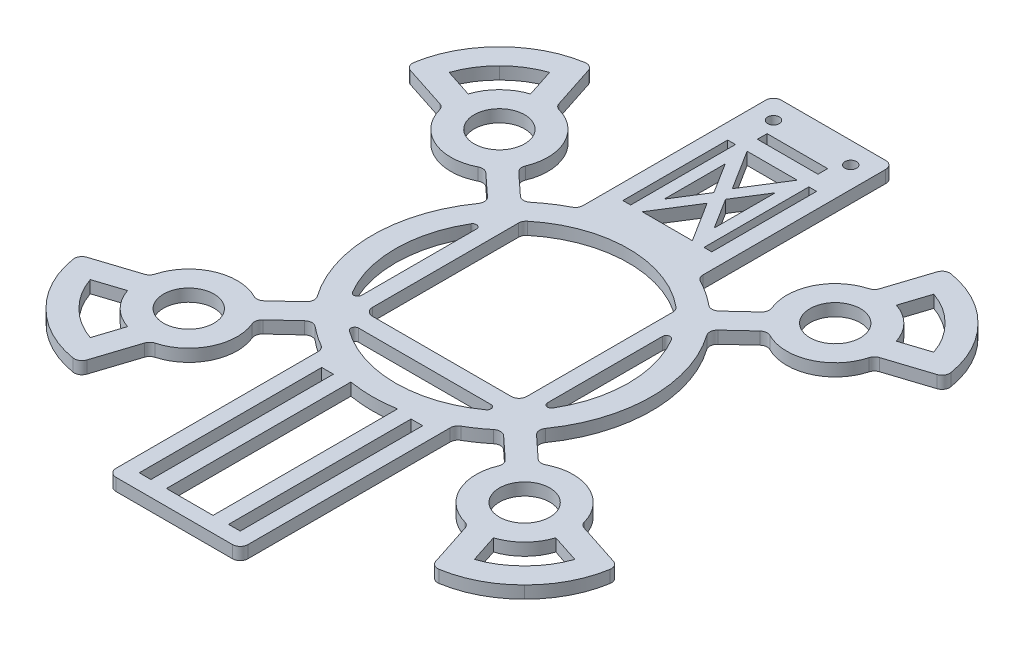
SolidWorks part; units mm, degrees
material "Mahogany"
ref_plane "Front Plane" through (0, 0, 0) normal (0, 0, 1) x (1, 0, 0)
ref_plane "Top Plane" through (0, 0, 0) normal (0, 1, 0) x (1, 0, 0)
ref_plane "Right Plane" through (0, 0, 0) normal (1, 0, 0) x (0, 0, -1)
sketch "DroneShadow" plane through (0, 0, 0) normal (0, 1, 0) x (1, 0, 0)
  line L0 (43.25, 80) -> (43.25, 0) construction
  line L5 (0, 0) -> (86.5, 0) construction
  line L6 (0, 0) -> (0, 80) construction
  line L7 (0, 80) -> (86.5, 80) construction
  line L8 (86.5, 0) -> (86.5, 80) construction
  line L9 (27.25, 76) -> (59.25, 76) construction
  line L10 (27.25, 76) -> (27.25, 12) construction
  line L11 (27.25, 12) -> (59.25, 12) construction
  line L12 (59.25, 76) -> (59.25, 12) construction
  line L13 (0, 80) -> (-14.1421, 94.1421) construction
  line L14 (0, 80) -> (-6.2176, 99.1576) construction
  line L15 (0, 80) -> (-19.1576, 86.2176) construction
  line L16 (0, 40) -> (86.5, 40) construction
  line L17 (0, 0) -> (-19.1576, -6.2176) construction
  line L18 (0, 0) -> (-6.2176, -19.1576) construction
  line L19 (0, 0) -> (-14.1421, -14.1421) construction
  line L20 (86.5, 0) -> (100.6421, -14.1421) construction
  line L21 (86.5, 0) -> (92.7176, -19.1576) construction
  line L22 (86.5, 0) -> (105.6576, -6.2176) construction
  line L23 (86.5, 80) -> (105.6576, 86.2176) construction
  line L24 (86.5, 80) -> (92.7176, 99.1576) construction
  line L25 (86.5, 80) -> (100.6421, 94.1421) construction
  circle A0 centre (0, 80) radius 5.5 construction
  arc A4 (-14.1421, 94.1421) -> (-6.2176, 99.1576) centre (0.358, 80) cw construction
  arc A5 (-14.1421, 94.1421) -> (-19.1576, 86.2176) centre (0, 79.642) ccw construction
  arc A6 (-14.1421, -14.1421) -> (-19.1576, -6.2176) centre (0, 0.358) cw construction
  arc A7 (-14.1421, -14.1421) -> (-6.2176, -19.1576) centre (0.358, 0) ccw construction
  circle A8 centre (0, 0) radius 5.5 construction
  circle A9 centre (86.5, 0) radius 5.5 construction
  arc A10 (100.6421, -14.1421) -> (92.7176, -19.1576) centre (86.142, 0) cw construction
  arc A11 (100.6421, -14.1421) -> (105.6576, -6.2176) centre (86.5, 0.358) ccw construction
  arc A12 (100.6421, 94.1421) -> (105.6576, 86.2176) centre (86.5, 79.642) cw construction
  arc A13 (100.6421, 94.1421) -> (92.7176, 99.1576) centre (86.142, 80) ccw construction
  circle A14 centre (86.5, 80) radius 5.5 construction
  point P12 (43.25, 76)
  dimension "D1" = 80
  dimension "D2" = 86.5
  dimension "D3" = 64
  dimension "D4" = 32
  dimension "D5" = 4
  dimension "D6" = 45
  dimension "D7" = 20
  dimension "D8" = 18.3
sketch "Sketch2" plane through (0, 0, 0) normal (0, 1, 0) x (1, 0, 0)
  line L0 (0, 40) -> (86.5, 40) construction
  line L1 (43.25, 80) -> (43.25, 0) construction
  line L2 (0, 40) -> (86.5, 40) construction
  line L3 (18.9494, 66.5609) -> (10.9456, 73.9632)
  line L4 (43.25, 80) -> (43.25, 0) construction
  line L5 (0, 80) -> (-14.1421, 94.1421) construction
  line L6 (0, 80) -> (-12.3659, 95.7593) construction
  line L15 (0, 80) -> (43.25, 40) construction
  line L16 (27.25, 76) -> (59.25, 76) construction
  line L17 (14.8755, 62.156) -> (6.8717, 69.5583)
  line L18 (14.8755, 62.156) -> (19.2989, 58.065) construction
  line L19 (27.25, 76) -> (59.25, 76) construction
  line L20 (18.9494, 66.5609) -> (23.3728, 62.4699) construction
  line L21 (-14.1421, -14.1421) -> (0, 0) construction
  line L22 (0, 80) -> (-15.7593, 92.3659) construction
  line L23 (-14.1421, 94.1421) -> (0, 80) construction
  line L24 (-15.7593, 92.3659) -> (-9.8339, 87.7164)
  line L25 (2.3218, 92.2825) -> (-2.1731, 106.1324)
  line L26 (-12.3659, 95.7593) -> (-7.7164, 89.8339)
  line L27 (9.3391, 70.6609) -> (-2.1731, 106.1324)
  line L28 (-26.1324, 82.1731) -> (9.3391, 70.6609)
  line L30 (-26.1324, 82.1731) -> (-12.2825, 77.6782)
  line L31 (0, 80) -> (-6.2176, 99.1576) construction
  line L33 (-3.8587, 91.8895) -> (-6.2176, 99.1576)
  line L34 (-11.8895, 83.8587) -> (-19.1576, 86.2176)
  line L35 (0, 0) -> (-15.7593, -12.3659) construction
  line L36 (18.9494, 13.4391) -> (23.3728, 17.5301) construction
  line L37 (14.8755, 17.844) -> (19.2989, 21.935) construction
  line L38 (0, 0) -> (-12.3659, -15.7593) construction
  line L39 (-11.8895, -3.8587) -> (-19.1576, -6.2176)
  line L40 (-3.8587, -11.8895) -> (-6.2176, -19.1576)
  line L41 (-26.1324, -2.1731) -> (-12.2825, 2.3218)
  line L42 (-12.3659, -15.7593) -> (-7.7164, -9.8339)
  line L43 (2.3218, -12.2825) -> (-2.1731, -26.1324)
  line L44 (-15.7593, -12.3659) -> (-9.8339, -7.7164)
  line L45 (14.8755, 17.844) -> (6.8717, 10.4417)
  line L46 (18.9494, 13.4391) -> (10.9456, 6.0368)
  line L47 (19.2989, 58.065) -> (19.2989, 21.935)
  line L48 (23.3728, 62.4699) -> (23.3728, 17.5301)
  line L49 (19.2989, 21.935) -> (67.2011, 21.935)
  line L50 (23.3728, 17.5301) -> (63.1272, 17.5301)
  line L51 (84.1782, -12.2825) -> (88.6731, -26.1324)
  line L52 (86.5, 0) -> (98.8659, -15.7593) construction
  line L53 (71.6245, 17.844) -> (67.2011, 21.935) construction
  line L54 (67.5506, 13.4391) -> (63.1272, 17.5301) construction
  line L55 (86.5, 0) -> (102.2593, -12.3659) construction
  line L56 (100.6421, 94.1421) -> (86.5, 80) construction
  line L57 (86.5, 80) -> (102.2593, 92.3659) construction
  line L58 (100.6421, -14.1421) -> (86.5, 0) construction
  line L59 (67.5506, 66.5609) -> (63.1272, 62.4699) construction
  line L60 (71.6245, 62.156) -> (67.2011, 58.065) construction
  line L61 (86.5, 80) -> (43.25, 40) construction
  line L62 (86.5, 80) -> (98.8659, 95.7593) construction
  line L63 (63.1272, 62.4699) -> (63.1272, 17.5301)
  line L64 (67.2011, 58.065) -> (67.2011, 21.935)
  line L65 (67.5506, 13.4391) -> (75.5544, 6.0368)
  line L66 (71.6245, 17.844) -> (79.6283, 10.4417)
  line L67 (102.2593, -12.3659) -> (96.3339, -7.7164)
  line L68 (98.8659, -15.7593) -> (94.2164, -9.8339)
  line L69 (112.6324, -2.1731) -> (98.7825, 2.3218)
  line L70 (90.3587, -11.8895) -> (92.7176, -19.1576)
  line L71 (98.3895, -3.8587) -> (105.6576, -6.2176)
  line L72 (98.3895, 83.8587) -> (105.6576, 86.2176)
  line L73 (90.3587, 91.8895) -> (92.7176, 99.1576)
  line L74 (112.6324, 82.1731) -> (98.7825, 77.6782)
  line L75 (98.8659, 95.7593) -> (94.2164, 89.8339)
  line L76 (84.1782, 92.2825) -> (88.6731, 106.1324)
  line L77 (102.2593, 92.3659) -> (96.3339, 87.7164)
  line L78 (71.6245, 62.156) -> (79.6283, 69.5583)
  line L79 (67.5506, 66.5609) -> (75.5544, 73.9632)
  circle A8 centre (43.25, 40) radius 36
  circle A9 centre (0, 80) radius 12.5
  circle A13 centre (43.25, 40) radius 30
  circle A14 centre (0, 80) radius 6.5
  circle A15 centre (0, 80) radius 6.5
  arc A18 (-6.2176, -19.1576) -> (-14.1421, -14.1421) centre (0.358, 0) cw
  arc A19 (-14.1421, 94.1421) -> (-19.1576, 86.2176) centre (0, 79.642) ccw construction
  arc A20 (-6.2176, 99.1576) -> (-14.1421, 94.1421) centre (0.358, 80) ccw construction
  arc A21 (-2.1731, 106.1324) -> (-18.385, 98.385) centre (0.358, 80) ccw
  arc A22 (-18.385, 98.385) -> (-26.1324, 82.1731) centre (0, 79.642) ccw
  arc A23 (-2.1731, 106.1324) -> (-18.385, 98.385) centre (0.358, 80) ccw
  arc A24 (-18.385, 98.385) -> (-26.1324, 82.1731) centre (0, 79.642) ccw
  arc A25 (-14.1421, 94.1421) -> (-19.1576, 86.2176) centre (0, 79.642) ccw
  arc A26 (-6.2176, 99.1576) -> (-14.1421, 94.1421) centre (0.358, 80) ccw
  arc A27 (-14.1421, -14.1421) -> (-19.1576, -6.2176) centre (0, 0.358) cw
  arc A28 (-18.385, -18.385) -> (-26.1324, -2.1731) centre (0, 0.358) cw
  arc A29 (-2.1731, -26.1324) -> (-18.385, -18.385) centre (0.358, 0) cw
  circle A30 centre (0, 0) radius 6.5
  circle A31 centre (0, 0) radius 12.5
  arc A32 (88.6731, -26.1324) -> (104.885, -18.385) centre (86.142, 0) ccw
  circle A33 centre (86.5, 0) radius 12.5
  circle A34 centre (86.5, 0) radius 6.5
  arc A35 (104.885, -18.385) -> (112.6324, -2.1731) centre (86.5, 0.358) ccw
  arc A36 (100.6421, -14.1421) -> (105.6576, -6.2176) centre (86.5, 0.358) ccw
  arc A37 (92.7176, 99.1576) -> (100.6421, 94.1421) centre (86.142, 80) cw
  arc A38 (100.6421, 94.1421) -> (105.6576, 86.2176) centre (86.5, 79.642) cw
  arc A39 (104.885, 98.385) -> (112.6324, 82.1731) centre (86.5, 79.642) cw
  arc A40 (88.6731, 106.1324) -> (104.885, 98.385) centre (86.142, 80) cw
  arc A41 (92.7176, -19.1576) -> (100.6421, -14.1421) centre (86.142, 0) ccw
  circle A42 centre (86.5, 80) radius 6.5
  circle A43 centre (86.5, 80) radius 12.5
  point P11 (13.9637, 8.8281)
  point P22 (-7.7164, 89.8339)
  point P27 (-9.8339, 87.7164)
  point P41 (-8.8388, 88.8388)
  point P75 (-8.8388, -8.8388)
  point P76 (-9.8339, -7.7164)
  point P77 (-7.7164, -9.8339)
  point P80 (43.25, 21.935)
  point P117 (43.25, 17.5301)
  point P132 (94.2164, -9.8339)
  point P133 (96.3339, -7.7164)
  point P134 (95.3388, -8.8388)
  point P135 (95.3388, 88.8388)
  point P136 (96.3339, 87.7164)
  point P137 (94.2164, 89.8339)
  point P138 (0, 0)
  point P139 (0, 0)
  point P140 (0, 0)
  point P141 (0, 0)
  dimension "D2" = 6
  dimension "D3" = 3
  dimension "D4" = 3
  dimension "D5" = 6
  dimension "D8" = 1.5
  dimension "D9" = 1.5
  dimension "D1" = 1
  dimension "D7" = 6
extrude "Base" add sketch "Sketch2" along normal blind 3.175 contours L45 A31 L46 A8 | A31 A30 | L39 A31 L41 A28 A29 L43 L40 A18 A27 | A26 L33 A9 L25 A23 A24 L30 L34 A25 | A9 A15 | A9 L17 A8 L3 | A43 A42 | L76 A43 L73 A37 A38 L72 L74 A39 A40 | A41 L70 A33 L51 A32 A35 L69 L71 A36 | A33 A34 | A33 L66 A8 L65 | L78 A43 L79 A8 | A8 A13 | L48 A13 L47 L49 | L63 L49 L48 L50 | L64 A13 L63 L49 | L63 A13 L49 | L49 A13 L48
sketch "Sketch3" plane through (0, 0, 0) normal (0, 1, 0) x (1, 0, 0)
  line L0 (43.25, -920) -> (43.25, 49080) construction
  line L1 (27.8, 122.8) -> (58.7, 122.8)
  line L2 (27.8, 122.8) -> (27.8, 72.5161)
  line L3 (58.7, 122.8) -> (58.7, 72.5161)
  line L4 (33.3, 117.3) -> (43.25, 117.3) construction
  line L5 (51.05, 111) -> (35.45, 111) construction
  line L6 (51.05, 111) -> (51.05, 123.6) construction
  line L7 (51.05, 123.6) -> (35.45, 123.6) construction
  line L8 (35.45, 111) -> (35.45, 123.6) construction
  line L9 (51.05, 111) -> (35.45, 123.6) construction
  line L10 (51.05, 123.6) -> (35.45, 111) construction
  line L11 (31.8, 117.3) -> (31.8, 122.8) construction
  line L12 (51.05, 113.5) -> (35.45, 113.5)
  line L13 (51.05, 113.5) -> (51.05, 111)
  line L14 (51.05, 111) -> (35.45, 111)
  line L15 (35.45, 113.5) -> (35.45, 111)
  line L16 (51.05, 113.5) -> (35.45, 111) construction
  line L17 (51.05, 111) -> (35.45, 113.5) construction
  line L18 (33.8, 107) -> (52.7, 107) construction
  line L19 (27.25, 76) -> (59.25, 76) construction
  line L20 (31.8, 107) -> (33.8, 107)
  line L21 (31.8, 107) -> (31.8, 80)
  line L22 (31.8, 80) -> (33.8, 80)
  line L23 (33.8, 107) -> (33.8, 80)
  line L24 (33.3, 118.8) -> (53.2, 118.8) construction
  line L25 (52.7, 107) -> (52.7, 80)
  line L26 (54.7, 80) -> (52.7, 80)
  line L27 (54.7, 107) -> (54.7, 80)
  line L28 (54.7, 107) -> (52.7, 107)
  line L58 (36.8, 107) -> (43.25, 96.7492)
  line L59 (36.8, 107) -> (49.7, 107)
  line L60 (33.8, 93.5) -> (52.7, 93.5) construction
  line L61 (36.8, 101.3669) -> (36.8, 85.6331)
  line L62 (36.8, 101.3669) -> (41.75, 93.5)
  line L63 (36.8, 85.6331) -> (41.75, 93.5)
  line L64 (36.8, 80) -> (49.7, 80)
  line L65 (36.8, 80) -> (43.25, 90.2508)
  line L66 (49.7, 80) -> (43.25, 90.2508)
  line L67 (49.7, 85.6331) -> (44.75, 93.5)
  line L68 (49.7, 101.3669) -> (44.75, 93.5)
  line L69 (49.7, 101.3669) -> (49.7, 85.6331)
  line L70 (49.7, 107) -> (43.25, 96.7492)
  circle A0 centre (43.25, 40) radius 36 construction
  circle A1 centre (33.3, 117.3) radius 1.5
  circle A2 centre (53.2, 117.3) radius 1.5
  arc A3 (58.7, 72.5161) -> (27.8, 72.5161) centre (43.25, 40) ccw
  point P4 (43.25, 122.8)
  point P5 (43.25, 117.3)
  point P22 (43.25, 112.25)
  point P38 (49.7, 93.5)
  point P43 (43.25, 100.0071)
  point P45 (43.25, 93.5)
  point P46 (0, 0)
  point P47 (40.8796, 93.5)
  point P49 (36.8, 93.5)
  point P53 (43.25, 80)
  point P57 (43.25, 107)
  dimension "D3" = 3
  dimension "D2" = 12.6
  dimension "D1" = 15.6
  dimension "D4" = 19.9
  dimension "D5" = 2.5
  dimension "D6" = 4
  dimension "D8" = 27
  dimension "D9" = 4
  dimension "D10" = 2
  dimension "D11" = 4
  dimension "D12" = 4
  dimension "D7" = 4
  dimension "D13" = 3
  dimension "D14" = 3
  dimension "D15" = 1.5
extrude "FrontPlatform" add sketch "Sketch3" along normal up to surface (3.175 mm away) up to face at (-11.3979, 3.175, 11.3979)
sketch "Sketch4" plane through (0, 0, 0) normal (0, 1, 0) x (1, 0, 0)
  line L1 (43.25, -960) -> (43.25, 49040) construction
  line L2 (26.25, -47) -> (60.25, -47)
  line L3 (26.25, -47) -> (26.25, 8.2667)
  line L4 (60.25, -47) -> (60.25, 8.2667)
  line L5 (53.25, 4) -> (53.25, -43)
  line L6 (30.25, 4) -> (33.25, 4)
  line L7 (30.25, 4) -> (30.25, -43)
  line L8 (30.25, -43) -> (33.25, -43)
  line L9 (33.25, 4) -> (33.25, -43)
  line L14 (56.25, -43) -> (53.25, -43)
  line L15 (56.25, 4) -> (56.25, -43)
  line L16 (56.25, 4) -> (53.25, 4)
  line L17 (26.25, 4) -> (60.25, 4) construction
  line L18 (26.25, -46) -> (43.25, -46) construction
  line L19 (43.25, -200920) -> (43.25, 249080) construction
  line L20 (49.25, 4.5035) -> (49.25, -43)
  line L22 (37.25, 4.5035) -> (37.25, -43)
  line L23 (37.25, -43) -> (49.25, -43)
  circle A0 centre (43.25, 40) radius 36 construction
  arc A1 (26.25, 8.2667) -> (37.25, 4.5035) centre (43.25, 40) ccw
  arc A2 (49.25, 4.5035) -> (60.25, 8.2667) centre (43.25, 40) ccw
  point P5 (43.25, -47)
  point P25 (43.25, -43)
  point P27 (46.3837, 4)
  point P31 (43.25, -5.4311)
  dimension "D5" = 4
  dimension "D3" = 3
  dimension "D1" = 3
  dimension "D4" = 4
  dimension "D6" = 26
  dimension "D7" = 50
  dimension "D2" = 4
extrude "Boss-Extrude4" add sketch "Sketch4" along normal up to surface (3.175 mm away) up to face at (-11.3979, 3.175, 11.3979)
fillet "Fillet1" radius 2 44 edges at (63.1272, 1.5875, -62.4699) (23.3728, 1.5875, -62.4699) (63.1272, 1.5875, -21.935) (23.3728, 1.5875, -21.935) (14.8755, 1.5875, -17.844) (6.8717, 1.5875, -10.4417) (-12.2825, 1.5875, -2.3218) (-26.1324, 1.5875, 2.1731) (-2.1731, 1.5875, 26.1324) (2.3218, 1.5875, 12.2825) (10.9456, 1.5875, -6.0368) (18.9494, 1.5875, -13.4391) (26.25, 1.5875, -8.2667) (26.25, 1.5875, 47) (60.25, 1.5875, 47) (67.5506, 1.5875, -13.4391) (60.25, 1.5875, -8.2667) (75.5544, 1.5875, -6.0368) (84.1782, 1.5875, 12.2825) (88.6731, 1.5875, 26.1324) (112.6324, 1.5875, 2.1731) (98.7825, 1.5875, -2.3218) (79.6283, 1.5875, -10.4417) (71.6245, 1.5875, -17.844) (71.6245, 1.5875, -62.156) (79.6283, 1.5875, -69.5583) (98.7825, 1.5875, -77.6782) (75.5544, 1.5875, -73.9632) (112.6324, 1.5875, -82.1731) (88.6731, 1.5875, -106.1324) (84.1782, 1.5875, -92.2825) (67.5506, 1.5875, -66.5609) (58.7, 1.5875, -72.5161) (58.7, 1.5875, -122.8) (27.8, 1.5875, -122.8) (27.8, 1.5875, -72.5161) (18.9494, 1.5875, -66.5609) (10.9456, 1.5875, -73.9632) (2.3218, 1.5875, -92.2825) (-2.1731, 1.5875, -106.1324) (-26.1324, 1.5875, -82.1731) (6.8717, 1.5875, -69.5583) (-12.2825, 1.5875, -77.6782) (14.8755, 1.5875, -62.156)
fillet "Fillet2" radius 1 6 edges at (19.2989, 1.5875, -21.935) (19.2989, 1.5875, -58.065) (63.1272, 1.5875, -17.5301) (23.3728, 1.5875, -17.5301) (67.2011, 1.5875, -58.065) (67.2011, 1.5875, -21.935)
equation "\"prop-dist-width\"= 86.5mm"
equation "\"prop-dist-length\"= 80mm"
equation "\"vent-width\"= 32mm"
equation "\"vent-length\"= 64mm"
equation "\"vent-offset-front\"= 4mm"
equation "\"T\"= 0.125in'Material Thickness"
equation "\"L_f\"= 20mm'Length of front platform"
equation "\"L_m\"= 70mm'Lenght of mid platform"
equation "\"L_b\"= 20mm'Length of back platform"
equation "\"W_min\"= round ( 1.25 * \"T\" )'Minimum width of parts"
equation "\"tof_c2c\"= 19.9mm'Center to center distance of TOF sensor hols"
equation "\"tof_d\"= 3mm'TOF hole diameter"
equation "\"tof_w\"= 12.6mm'TOF width"
equation "\"tof_l\"= 15.6mm'TOF length"
equation "\"pin_w\"= 2.3mm'A standard IO Pin socket width"
equation "\"pin_l\"= 2.5mm'A standard IO Pin socket length"
equation "\"esp_pin_num\"= 8'Number of pins on one side of the ESP"
equation "\"esp_l\"= 40mm'ESP length"
equation "\"esp_w\"= 27mm'ESP width"
equation "\"esp_pin_inset\"= 3mm'Distance that ESP pins are inset"
equation "\"bat_l\"= 27mm'Battery length"
equation "\"bat_w\"= 20mm'Battery width"
equation "\"bat_h\"= 6mm'Battery thickness"
equation "\"boost_w\"= 17.2mm"
equation "\"boost_l\"= 37mm"
equation "\"boost_hole_inset\"= 2.2mm"
equation "\"boost_hole_dist\"= 7mm"
equation "\"boost_hole_d\"= 2mm"
equation "\"D1@DroneShadow\" = \"prop-dist-length\""
equation "\"D2@DroneShadow\" = \"prop-dist-width\""
equation "\"D3@DroneShadow\" = \"vent-length\""
equation "\"D4@DroneShadow\" = \"vent-width\""
equation "\"D5@DroneShadow\" = \"vent-offset-front\""
equation "\"D1@Base\" = \"T\""
equation "\"D2@Sketch3\"=\"tof_w\""
equation "\"D1@Sketch3\"=\"tof_l\""
equation "\"D3@Sketch3\"=\"tof_d\""
equation "\"D4@Sketch3\"=\"tof_c2c\""
equation "\"D5@Sketch3\"=\"pin_l\""
equation "\"front_ext\"= 45mm"
equation "\"back_ext\"= 60mm"
equation "\"D8@Sketch3\"=\"bat_l\""
equation "\"D3@Sketch4\"=\"esp_pin_inset\""
equation "\"D7@Sketch4\"=\"esp_l\"+10"
